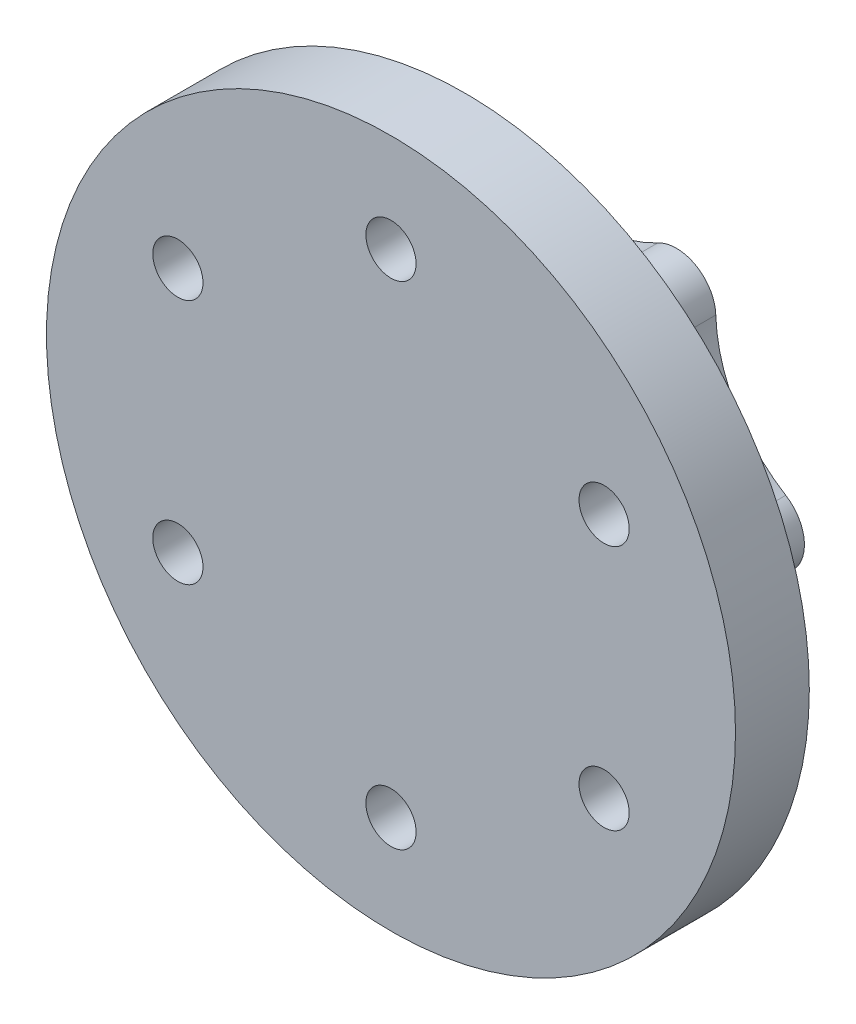
SolidWorks part; units mm, degrees
ref_plane "Front Plane" through (0, 0, 0) normal (1, 0, 0) x (0, 1, 0)
ref_plane "Top Plane" through (0, 0, 0) normal (0, 0, 1) x (0, 1, 0)
ref_plane "Right Plane" through (0, 0, 0) normal (0, 1, 0) x (-1, 0, 0)
sketch "Sketch2" plane through (0, 0, 0) normal (0, 0, 1) x (0, 1, 0)
  line L0 (0, 0) -> (45.2618, 26.1319) construction
  line L1 (0, 0) -> (47.7277, 0) construction
  line L2 (0, 0) -> (-24.1884, 13.9652) construction
  line L3 (0, 0) -> (-20.6417, 0) construction
  arc A1 (3.4023, 20.1034) -> (-3.4023, 20.1034) centre (0, 18) ccw
  arc A2 (19.1112, 7.1053) -> (15.709, 12.9982) centre (15.5885, 9) ccw
  arc A3 (15.709, -12.9982) -> (19.1112, -7.1053) centre (15.5885, -9) ccw
  arc A4 (-3.4023, -20.1034) -> (3.4023, -20.1034) centre (0, -18) ccw
  arc A5 (-19.1112, -7.1053) -> (-15.709, -12.9982) centre (-15.5885, -9) ccw
  arc A6 (-15.709, 12.9982) -> (-19.1112, 7.1053) centre (-15.5885, 9) ccw
  circle A8 centre (0, 18) radius 2.05 construction
  circle A9 centre (15.5885, 9) radius 2.05 construction
  circle A10 centre (15.5885, -9) radius 2.05 construction
  circle A11 centre (0, -18) radius 2.05 construction
  circle A12 centre (-15.5885, -9) radius 2.05 construction
  circle A13 centre (-15.5885, 9) radius 2.05 construction
  arc A14 (-13.2682, 13.2729) -> (-15.709, 12.9982) centre (-16.1608, 27.9914) cw
  arc A15 (-17.3217, 0) -> (-19.1112, 7.1053) centre (-32.3217, 0) ccw
  arc A16 (4.8606, 18.1271) -> (3.4023, 20.1034) centre (16.1608, 27.9914) cw
  arc A17 (-13.2682, 13.2729) -> (-3.4023, 20.1034) centre (-16.1608, 27.9914) ccw
  arc A18 (17.3217, 0) -> (19.1112, 7.1053) centre (32.3217, 0) cw
  arc A19 (4.8606, 18.1271) -> (15.709, 12.9982) centre (16.1608, 27.9914) ccw
  arc A20 (13.2682, -13.2729) -> (15.709, -12.9982) centre (16.1608, -27.9914) cw
  arc A21 (17.3217, 0) -> (19.1112, -7.1053) centre (32.3217, 0) ccw
  arc A22 (-13.2682, -13.2729) -> (-3.4023, -20.1034) centre (-16.1608, -27.9914) cw
  arc A23 (13.2682, -13.2729) -> (3.4023, -20.1034) centre (16.1608, -27.9914) ccw
  arc A24 (-17.3217, 0) -> (-19.1112, -7.1053) centre (-32.3217, 0) cw
  arc A25 (-13.2682, -13.2729) -> (-15.709, -12.9982) centre (-16.1608, -27.9914) ccw
  point P16 (0, 0)
  point P31 (0, 0)
  dimension "D1" = 8
  dimension "D5" = 4.1
  dimension "D8" = 15
  dimension "D2" = 18
  dimension "D3" = 30
  dimension "D6" = 6
  dimension "D4" = 6
  dimension "D7" = 6
extrude "Boss-Extrude1" add sketch "Sketch2" along normal blind 12.5
sketch "Sketch4" plane through (0, 0, 0) normal (0, 0, 1) x (0, 1, 0)
  circle A0 centre (-15.5885, 9) radius 5
  circle A1 centre (0, 18) radius 5
  circle A2 centre (15.5885, 9) radius 5
  circle A3 centre (15.5885, -9) radius 5
  circle A4 centre (0, -18) radius 5
  circle A5 centre (-15.5885, -9) radius 5
  dimension "D1" = 10
  dimension "D2" = 6
extrude "Cut-Extrude1" cut sketch "Sketch4" against normal blind 9.3 from surface at 12.5 starting at face at (0, 0, 12.5)
sketch "Sketch6" plane through (0, 0, 0) normal (0, 0, 1) x (0, 1, 0)
  circle A0 centre (0, 0) radius 35
  dimension "D1" = 70
extrude "Boss-Extrude2" add sketch "Sketch6" along normal blind 7.5 from surface at 12.5 starting at face at (0, 0, 12.5)
sketch "Sketch9" plane through (0, 0, 0) normal (0, 0, 1) x (0, 1, 0)
  line L0 (0, 0) -> (12.5, 21.6506) construction
  line L1 (0, 0) -> (0, 16.4481) construction
  circle A1 centre (12.5, 21.6506) radius 2.55
  circle A2 centre (25, 0) radius 2.55
  circle A3 centre (12.5, -21.6506) radius 2.55
  circle A4 centre (-12.5, -21.6506) radius 2.55
  circle A5 centre (-25, 0) radius 2.55
  circle A6 centre (-12.5, 21.6506) radius 2.55
  dimension "D1" = 25
  dimension "D2" = 5.1
  dimension "D3" = 30
extrude "Cut-Extrude5" cut sketch "Sketch9" against normal blind 12 from surface at 20 starting at face at (35, 0, 20)
sketch "Sketch5" plane through (0, 0, 0) normal (0, 0, 1) x (0, 1, 0)
  circle A8 centre (-15.5885, 9) radius 2.05
  circle A9 centre (0, 18) radius 2.05
  circle A10 centre (15.5885, 9) radius 2.05
  circle A11 centre (15.5885, -9) radius 2.05
  circle A12 centre (0, -18) radius 2.05
  circle A13 centre (-15.5885, -9) radius 2.05
  dimension "D1" = 4.1
  dimension "D2" = 6
extrude "Cut-Extrude6" cut sketch "Sketch5" along normal blind 10
